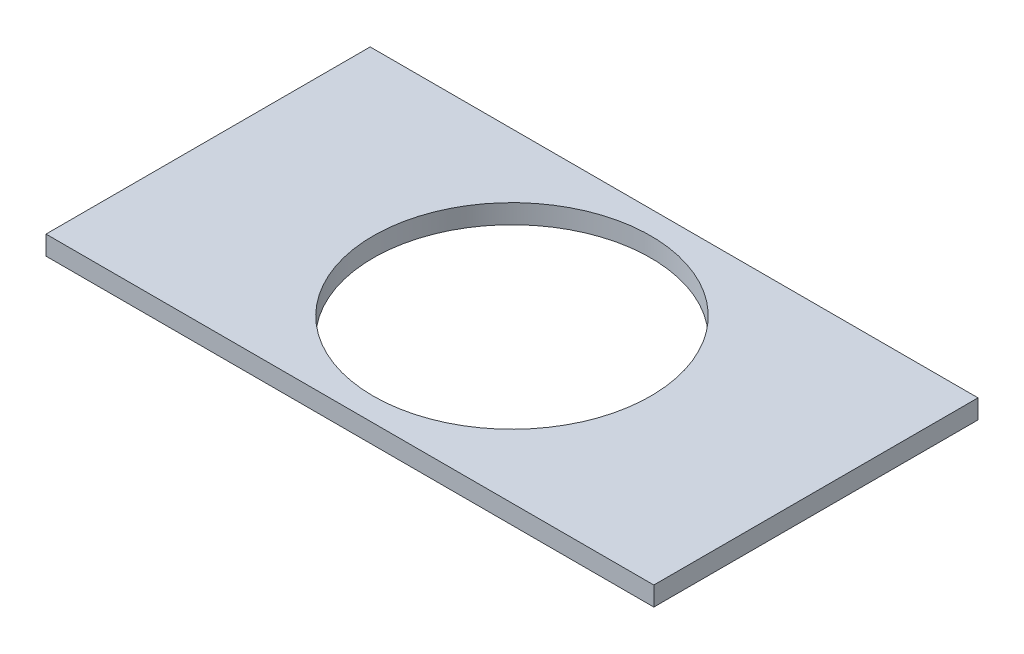
SolidWorks part; units mm, degrees
ref_plane "Front Plane" through (0, 0, 0) normal (0, 0, 1) x (1, 0, 0)
ref_plane "Top Plane" through (0, 0, 0) normal (0, 1, 0) x (1, 0, 0)
ref_plane "Right Plane" through (0, 0, 0) normal (1, 0, 0) x (0, 0, -1)
sketch "Sketch1" plane through (0, 0, 0) normal (0, 1, 0) x (1, 0, 0)
  line L1 (-47.625, 25.4) -> (47.625, 25.4)
  line L2 (-47.625, 25.4) -> (-47.625, -25.4)
  line L3 (-47.625, -25.4) -> (47.625, -25.4)
  line L4 (47.625, 25.4) -> (47.625, -25.4)
  line L5 (-47.625, 25.4) -> (47.625, -25.4) construction
  line L6 (-47.625, -25.4) -> (47.625, 25.4) construction
  point P0 (0, 0)
  dimension "D1" = 50.8
  dimension "D2" = 95.25
extrude "Boss-Extrude1" add sketch "Sketch1" along normal blind 3
sketch "Sketch2" plane through (0, 3, 0) normal (0, 1, 0) x (1, 0, 0)
  circle A0 centre (0, 0) radius 21.75
  dimension "D1" = 43.5
extrude "Cut-Extrude1" cut sketch "Sketch2" against normal through all both and the other way through all
